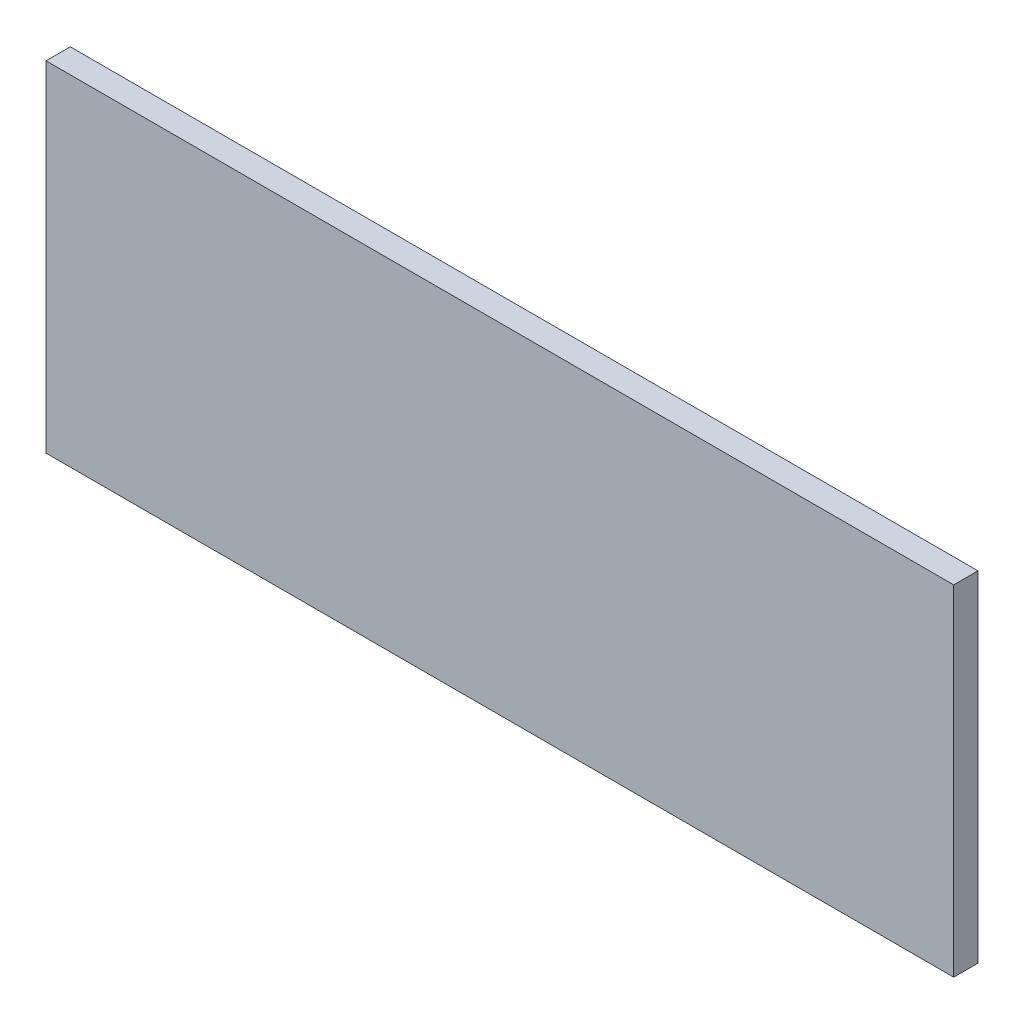
SolidWorks part; units mm, degrees
ref_plane "Plan de face" through (0, 0, 0) normal (0, 0, 1) x (1, 0, 0)
ref_plane "Plan de dessus" through (0, 0, 0) normal (0, 1, 0) x (1, 0, 0)
ref_plane "Plan de droite" through (0, 0, 0) normal (1, 0, 0) x (0, 0, -1)
sketch "Esquisse1" plane through (0, 0, 0) normal (0, 0, 1) x (1, 0, 0)
  line L1 (0, 0) -> (374, 0)
  line L2 (0, 0) -> (0, 140)
  line L3 (0, 140) -> (374, 140)
  line L4 (374, 0) -> (374, 140)
  dimension "D1" = 140
  dimension "D2" = 374
extrude "Boss.-Extru.1" add sketch "Esquisse1" along normal blind 10
